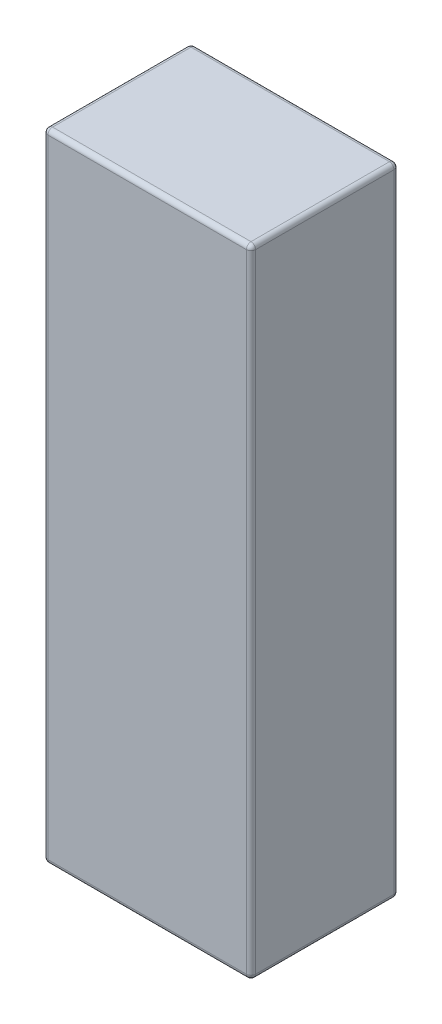
SolidWorks part; units mm, degrees
ref_plane "Front Plane" through (0, 0, 0) normal (0, 0, 1) x (1, 0, 0)
ref_plane "Top Plane" through (0, 0, 0) normal (0, 1, 0) x (1, 0, 0)
ref_plane "Right Plane" through (0, 0, 0) normal (1, 0, 0) x (0, 0, -1)
sketch "Sketch1" plane through (0, 0, 0) normal (0, 0, 1) x (1, 0, 0)
  line L1 (-22.5, 69) -> (22.5, 69)
  line L2 (-22.5, 69) -> (-22.5, -69)
  line L3 (-22.5, -69) -> (22.5, -69)
  line L4 (22.5, 69) -> (22.5, -69)
  line L5 (-22.5, 69) -> (22.5, -69) construction
  line L6 (-22.5, -69) -> (22.5, 69) construction
  point P0 (0, 0)
extrude "Boss-Extrude1" add sketch "Sketch1" along normal blind 32
fillet "Fillet1" radius 1 12 edges at (0, 69, 0) (0, 69, 32) (22.5, 69, 16) (22.5, 0, 32) (22.5, -69, 16) (0, -69, 32) (0, -69, 0) (-22.5, -69, 16) (22.5, 0, 0) (-22.5, 0, 32) (-22.5, 0, 0) (-22.5, 69, 16)
sketch "Sketch2" plane through (0, 0, 0) normal (0, 0, -1) x (-1, 0, 0)
  text T0 "<b>BATTERY</b>"
extrude "Cut-Extrude1" cut sketch "Sketch2" against normal blind 2
